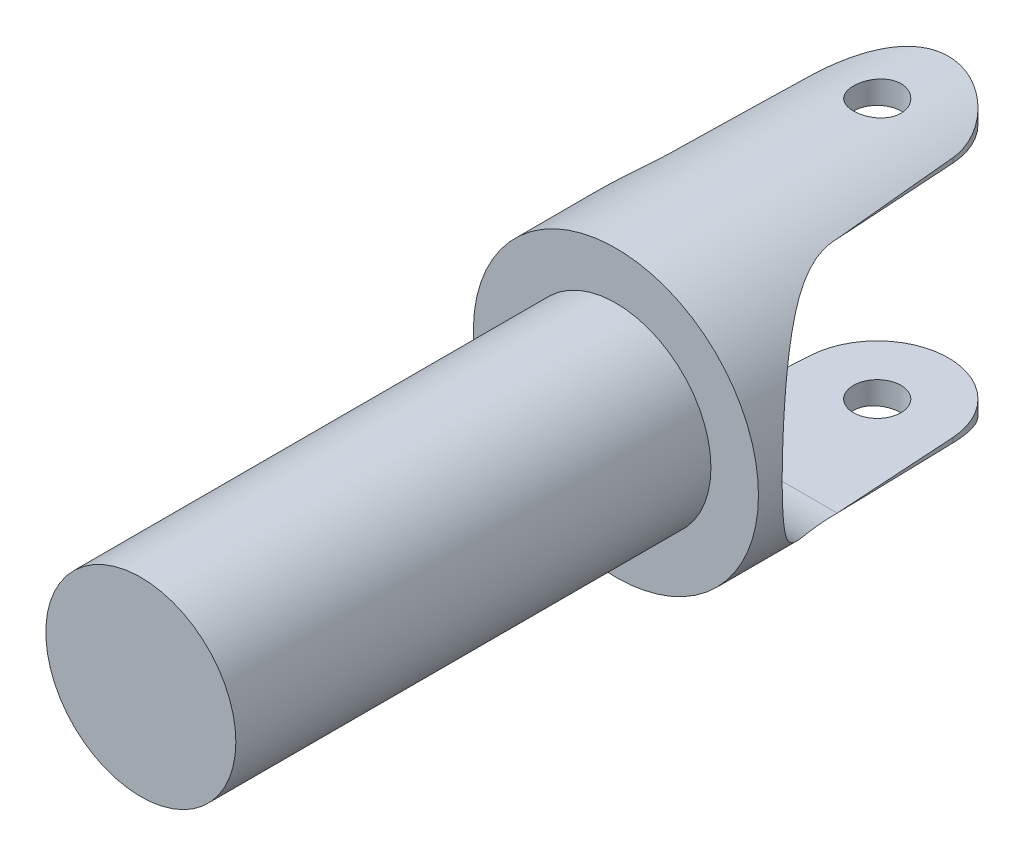
SolidWorks part; units mm, degrees
ref_plane "Front Plane" through (0, 0, 0) normal (0, 0, 1) x (1, 0, 0)
ref_plane "Top Plane" through (0, 0, 0) normal (0, 1, 0) x (1, 0, 0)
ref_plane "Right Plane" through (0, 0, 0) normal (1, 0, 0) x (0, 0, -1)
sketch "Base Sketch" plane through (0, 0, 0) normal (0, 0, 1) x (1, 0, 0)
  circle A0 centre (0, 0) radius 30
  dimension "D1" = 60
extrude "Base Extrude" add sketch "Base Sketch" along normal blind 30
sketch "Pin Sketch" plane through (0, 0, 30) normal (0, 0, 1) x (1, 0, 0)
  circle A0 centre (0, 0) radius 20
  dimension "D1" = 40
extrude "Pin Extrude" add sketch "Pin Sketch" along normal blind 100
sketch "Side Cut Sketch" plane through (0, 0, 0) normal (1, 0, 0) x (0, 0, -1)
  circle A0 centre (0, 0) radius 25
  dimension "D1" = 50
extrude "Side Cut" cut sketch "Side Cut Sketch" against normal up to surface and the other way up to surface up to face at (30, 0, 30) other way up to face at (30, 0, 30)
ref_plane "Wing Cutoff Plane" through (0, 25, 0) normal (0, 1, 0) x (1, 0, 0)
sketch "Wing Sketch" plane through (0, 25, 0) normal (0, 1, 0) x (1, 0, 0)
  line L0 (16.5831, 0) -> (-16.5831, 0) construction
  line L1 (-16.5831, 0) -> (-14.9711, 25.9307)
  line L2 (16.5831, 0) -> (14.9711, 25.9307)
  line L3 (-14.9711, 25.9307) -> (14.9711, 25.9307) construction
  line L4 (-16.5831, 0) -> (16.5831, 0)
  arc A0 (14.9711, 25.9307) -> (-14.9711, 25.9307) centre (0, 25) ccw
  dimension "D1" = 30
  dimension "D2" = 25
extrude "Wing Extrude" add sketch "Wing Sketch" along normal up to surface (0.9974 mm away)
mirror "Wing Mirror" about plane through (0, 0, 0) normal (0, 1, 0) of "Wing Extrude"
sketch "Pin Hole Sketch" plane through (0, 25, 0) normal (0, -1, 0) x (1, 0, 0)
  circle A0 centre (0, -25) radius 5
  arc A1 (-14.9711, -25.9307) -> (14.9711, -25.9307) centre (0, -25) ccw construction
  dimension "D1" = 10
extrude "Pin Hole Cut" cut sketch "Pin Hole Sketch" along normal through all both and the other way through all
